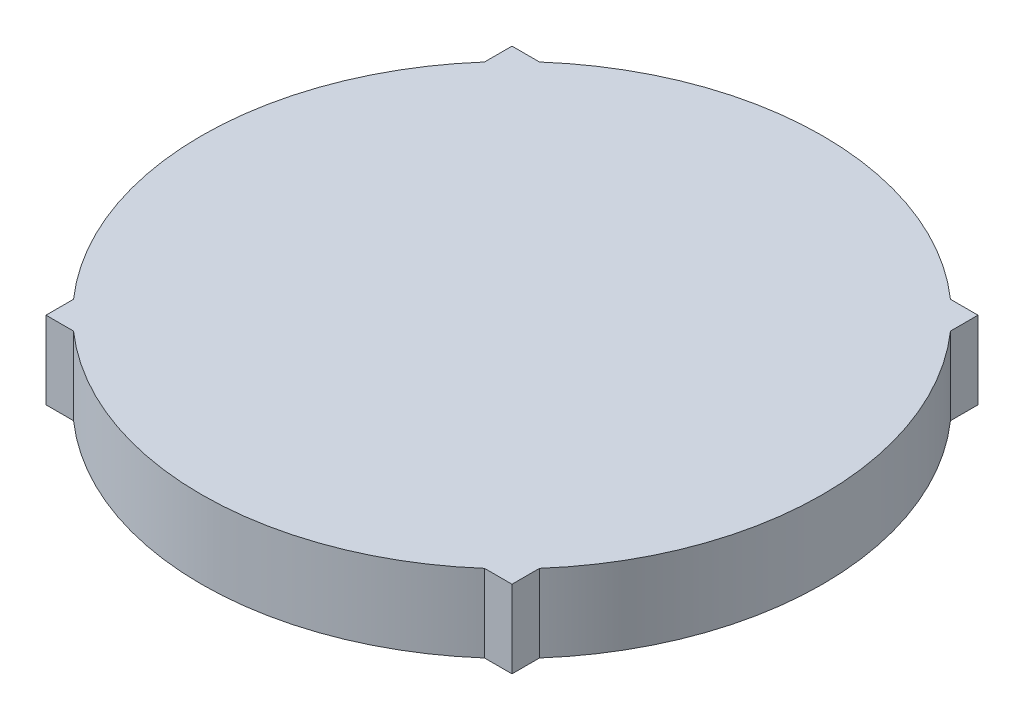
SolidWorks part; units mm, degrees
ref_plane "Front Plane" through (0, 0, 0) normal (0, 0, 1) x (1, 0, 0)
ref_plane "Top Plane" through (0, 0, 0) normal (0, 1, 0) x (1, 0, 0)
ref_plane "Right Plane" through (0, 0, 0) normal (1, 0, 0) x (0, 0, -1)
sketch "Sketch1" plane through (0, -66.8172, 0) normal (0, -1, 0) x (1, 0, 0)
  line L0 (26.4679, -26.475) -> (26.4679, -25.3503) construction
  line L1 (25.3432, -26.475) -> (26.4679, -26.475) construction
  line L2 (7.4179, -25.3503) -> (7.4179, -26.475) construction
  line L3 (7.4179, -26.475) -> (8.5427, -26.475) construction
  line L4 (26.4679, -8.5497) -> (26.4679, -7.425) construction
  line L5 (26.4679, -7.425) -> (25.3432, -7.425) construction
  line L6 (8.5427, -7.425) -> (7.4179, -7.425) construction
  line L7 (7.4179, -7.425) -> (7.4179, -8.5497) construction
  line L8 (26.4679, -26.475) -> (26.4679, -25.3503)
  line L9 (25.3432, -26.475) -> (26.4679, -26.475)
  line L10 (7.4179, -25.3503) -> (7.4179, -26.475)
  line L11 (7.4179, -26.475) -> (8.5427, -26.475)
  line L12 (26.4679, -8.5497) -> (26.4679, -7.425)
  line L13 (26.4679, -7.425) -> (25.3432, -7.425)
  line L14 (8.5427, -7.425) -> (7.4179, -7.425)
  line L15 (7.4179, -7.425) -> (7.4179, -8.5497)
  arc A0 (8.5427, -26.475) -> (25.3432, -26.475) centre (16.9429, -16.95) ccw construction
  arc A1 (26.4679, -25.3503) -> (26.4679, -8.5497) centre (16.9429, -16.95) ccw construction
  arc A2 (7.4179, -8.5497) -> (7.4179, -25.3503) centre (16.9429, -16.95) ccw construction
  arc A3 (25.3432, -7.425) -> (8.5427, -7.425) centre (16.9429, -16.95) ccw construction
  arc A4 (8.5427, -26.475) -> (25.3432, -26.475) centre (16.9429, -16.95) ccw
  arc A5 (26.4679, -25.3503) -> (26.4679, -8.5497) centre (16.9429, -16.95) ccw
  arc A6 (7.4179, -8.5497) -> (7.4179, -25.3503) centre (16.9429, -16.95) ccw
  arc A7 (25.3432, -7.425) -> (8.5427, -7.425) centre (16.9429, -16.95) ccw
extrude "Boss-Extrude1" add sketch "Sketch1" against normal blind 3.175
sketch "Sketch2" plane through (0, -66.8172, 0) normal (0, -1, 0) x (1, 0, 0)
  circle A0 centre (16.9429, -16.95) radius 6.2992
  dimension "D1" = 12.5984
extrude "Cut-Extrude1" cut sketch "Sketch2" against normal blind 2.54
